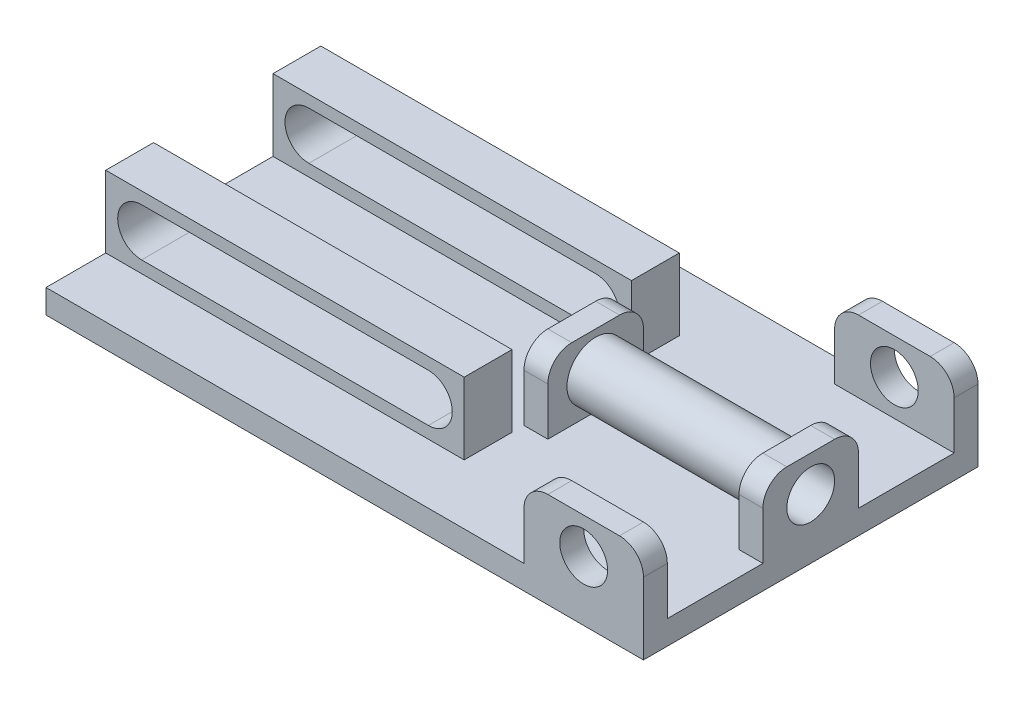
SolidWorks part; units mm, degrees
ref_plane "Front Plane" through (0, 0, 0) normal (0, 0, 1) x (1, 0, 0)
ref_plane "Top Plane" through (0, 0, 0) normal (0, 1, 0) x (1, 0, 0)
ref_plane "Right Plane" through (0, 0, 0) normal (1, 0, 0) x (0, 0, -1)
sketch "Sketch1" plane through (0, 0, 0) normal (0, 1, 0) x (1, 0, 0)
  line L1 (-125, -70) -> (125, -70)
  line L2 (-125, -70) -> (-125, 70)
  line L3 (-125, 70) -> (125, 70)
  line L4 (125, -70) -> (125, 70)
  line L5 (-125, -70) -> (125, 70) construction
  line L6 (-125, 70) -> (125, -70) construction
  point P0 (0, 0)
extrude "Boss-Extrude1" add sketch "Sketch1" along normal blind 10
sketch "Sketch2" plane through (0, 10, 0) normal (0, 1, 0) x (1, 0, 0)
  line L0 (125, 0) -> (125, 20)
  line L1 (125, 70) -> (75, 70)
  line L2 (125, 70) -> (125, 50)
  line L3 (125, 50) -> (75, 50)
  line L4 (75, 70) -> (75, 50)
  line L5 (125, -70) -> (75, -70)
  line L6 (125, -70) -> (125, -50)
  line L7 (125, -50) -> (75, -50)
  line L8 (75, -70) -> (75, -50)
  line L9 (125, -70) -> (125, 70) construction
  line L10 (125, 20) -> (105, 20)
  line L11 (105, 20) -> (105, -20)
  line L12 (105, -20) -> (125, -20)
  line L13 (125, -20) -> (125, 0)
  line L15 (-125, 70) -> (-125, -70) construction
  line L16 (-125, -45) -> (25, -45)
  line L17 (25, -45) -> (25, -25)
  line L18 (25, -25) -> (-125, -25)
  line L19 (-125, -25) -> (-125, -45)
  line L21 (-125, 25) -> (-125, 45)
  line L22 (25, 25) -> (-125, 25)
  line L23 (25, 45) -> (25, 25)
  line L24 (-125, 45) -> (25, 45)
  line L25 (-125, 70) -> (-125, 45)
  line M15 (125, -70) -> (125, 70)
  line M16 (125, 70) -> (-125, 70)
  line M17 (-125, 70) -> (-125, -70)
  line M18 (-125, -70) -> (125, -70)
extrude "Boss-Extrude2" add sketch "Sketch2" along normal blind 30 contours L24 L22 L23 M17 | L17 L18 L16 M17 | L11 L12 L10 M15 | L4 L3 M16 M15 | L8 L7 M18 M15
sketch "Sketch3" plane through (0, 0, 45) normal (0, 0, 1) x (1, 0, 0)
  line L0 (25, 25) -> (10, 25) construction
  line L1 (25, 40) -> (25, 10) construction
  line L2 (-125, 25) -> (-110, 25) construction
  line L3 (-125, 40) -> (-125, 10) construction
  line L4 (10, 35) -> (-110, 35)
  line L5 (10, 15) -> (-110, 15)
  arc A0 (10, 15) -> (10, 35) centre (10, 25) ccw
  arc A1 (-110, 35) -> (-110, 15) centre (-110, 25) ccw
extrude "Cut-Extrude1" cut sketch "Sketch3" against normal blind 120
sketch "Sketch4" plane through (0, 0, 70) normal (0, 0, 1) x (1, 0, 0)
  line L0 (75, 10) -> (125, 40) construction
  circle A0 centre (100, 25) radius 10
extrude "Cut-Extrude2" cut sketch "Sketch4" against normal blind 150
sketch "Sketch6" plane through (0, 10, 0) normal (0, 1, 0) x (1, 0, 0)
  line L0 (125, 20) -> (105, 20) construction
  line L1 (115, 20) -> (105, 20)
  line L2 (115, 20) -> (115, -20)
  line L3 (115, -20) -> (105, -20)
  line L4 (105, 20) -> (105, -20)
extrude "Cut-Extrude4" cut sketch "Sketch6" along normal blind 150
sketch "Sketch7" plane through (125, 0, 0) normal (1, 0, 0) x (0, 0, -1)
  line L0 (-20, 10) -> (20, 40) construction
  circle A0 centre (0, 25) radius 10
extrude "Cut-Extrude5" cut sketch "Sketch7" against normal blind 150
sketch "Sketch8" plane through (115, 0, 0) normal (-1, 0, 0) x (0, 0, 1)
  circle A0 centre (0, 25) radius 10
  circle A1 centre (0, 25) radius 12
extrude "Boss-Extrude3" add sketch "Sketch8" along normal blind 80
sketch "Sketch9" plane through (35, 0, 0) normal (-1, 0, 0) x (0, 0, 1)
  line L1 (20, 40) -> (-20, 40)
  line L2 (20, 40) -> (20, 10)
  line L3 (20, 10) -> (-20, 10)
  line L4 (-20, 40) -> (-20, 10)
  circle A0 centre (0, 25) radius 10
extrude "Boss-Extrude4" add sketch "Sketch9" along normal blind 10
fillet "Fillet1" radius 10 2 edges at (30, 40, 20) (30, 40, -20)
fillet "Fillet2" radius 10 2 edges at (120, 40, 20) (120, 40, -20)
fillet "Fillet3" radius 10 4 edges at (75, 40, 60) (125, 40, 60) (75, 40, -60) (125, 40, -60)
sketch "Sketch13" plane through (0, 10, 0) normal (0, 1, 0) x (1, 0, 0)
  line L0 (75, 70) -> (75, 50) construction
  line L1 (75, 60) -> (125, 60)
  line L2 (75, 60) -> (75, 35)
  line L3 (75, 35) -> (125, 35)
  line L4 (125, 60) -> (125, 35)
  line L5 (125, 20) -> (125, 50) construction
  line L6 (75, -70) -> (75, -50) construction
  line L7 (75, -60) -> (125, -60)
  line L8 (75, -60) -> (75, -37.7557)
  line L9 (75, -37.7557) -> (125, -37.7557)
  line L10 (125, -60) -> (125, -37.7557)
  line L11 (125, -50) -> (125, -20) construction
extrude "Cut-Extrude6" cut sketch "Sketch13" along normal blind 40
